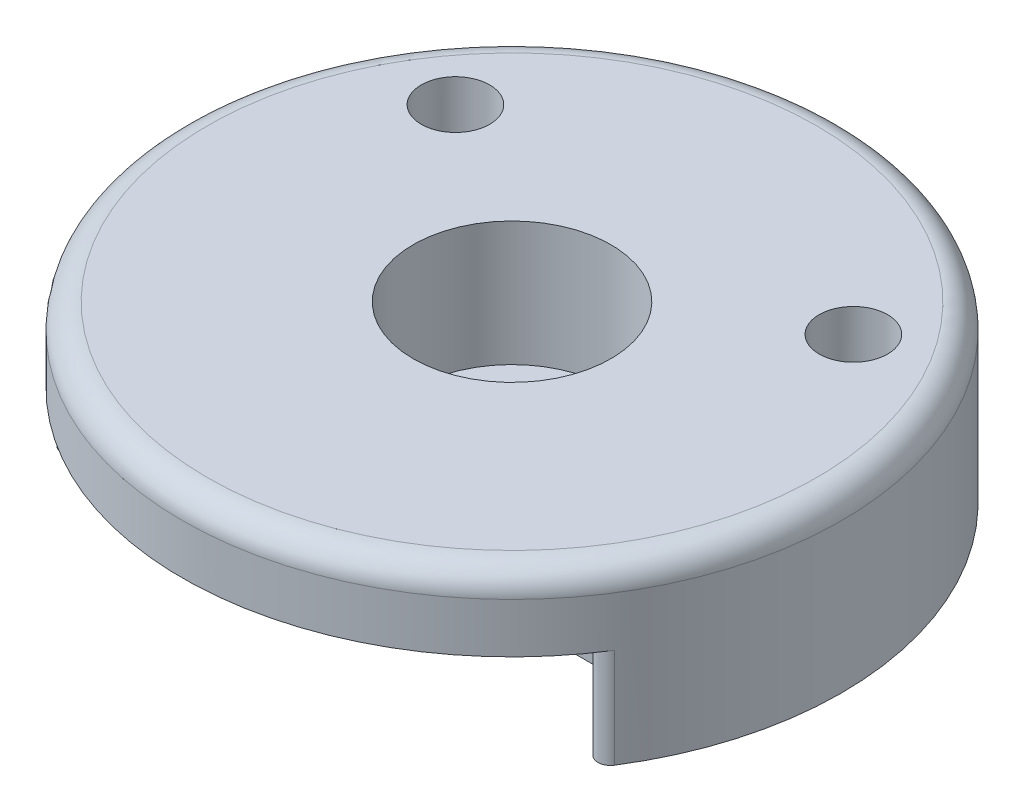
SolidWorks part; units mm, degrees
material "PVC 0.007 Plasticized"
ref_plane "Front Plane" through (0, 0, 0) normal (0, 0, 1) x (1, 0, 0)
ref_plane "Top Plane" through (0, 0, 0) normal (0, 1, 0) x (1, 0, 0)
ref_plane "Right Plane" through (0, 0, 0) normal (1, 0, 0) x (0, 0, -1)
sketch "Sketch2" plane through (0, 0, 0) normal (0, 1, 0) x (1, 0, 0)
  circle A0 centre (0, 0) radius 13.25
  dimension "D1" = 26.5
extrude "Boss-Extrude1" add sketch "Sketch2" along normal blind 7
sketch "Sketch3" plane through (0, 7, 0) normal (0, 1, 0) x (1, 0, 0)
  circle A0 centre (0, 0) radius 3.975
  dimension "D1" = 7.95
extrude "Cut-Extrude1" cut sketch "Sketch3" against normal blind 5
sketch "Sketch4" plane through (0, 0, 0) normal (0, -1, 0) x (1, 0, 0)
  line L1 (-10.275, 8.025) -> (10.275, 8.025)
  line L2 (-10.275, 8.025) -> (-10.275, -8.025)
  line L3 (-10.275, -8.025) -> (10.275, -8.025)
  line L4 (10.275, 8.025) -> (10.275, -8.025)
  line L5 (-10.275, 8.025) -> (10.275, -8.025) construction
  line L6 (-10.275, -8.025) -> (10.275, 8.025) construction
  point P0 (0, 0)
  dimension "D1" = 16.05
  dimension "D2" = 20.55
extrude "Cut-Extrude2" cut sketch "Sketch4" against normal blind 1
sketch "Sketch5" plane through (0, 1, 0) normal (0, -1, 0) x (1, 0, 0)
  line L0 (-8, -5.725) -> (8, -5.725) construction
  line L1 (10.275, 8.025) -> (-10.275, 8.025) construction
  circle A0 centre (-8, -5.725) radius 1.375
  circle A1 centre (8, -5.725) radius 1.375
  point P4 (0, -5.725)
  dimension "D1" = 2.75
  dimension "D2" = 16
  dimension "D3" = 13.75
extrude "Cut-Extrude3" cut sketch "Sketch5" against normal up to surface (6 mm away) up to face at (0, 7, 3.975)
fillet "Fillet1" radius 1 1 edges at (0, 7, 13.25)
sketch "Sketch6" plane through (0, 1, 0) normal (0, -1, 0) x (1, 0, 0)
  line L0 (10.275, -8.025) -> (10.275, 8.025) construction
  line L1 (10.275, 5) -> (-10.275, 5)
  line L2 (10.275, 5) -> (10.275, 13.25)
  line L3 (10.275, 13.25) -> (-10.275, 13.25)
  line L4 (-10.275, 5) -> (-10.275, 13.25)
  line L5 (-10.275, 8.025) -> (-10.275, -8.025) construction
  circle A0 centre (0, 0) radius 13.25 construction
  dimension "D1" = 5
extrude "Cut-Extrude5" cut sketch "Sketch6" against normal blind 3 and the other way up to surface (1 mm away) other way up to face at (0, 0, 0)
fillet "Fillet2" radius 0.5 2 edges at (10.275, 2, 8.3658) (-10.275, 2, 8.3658)
